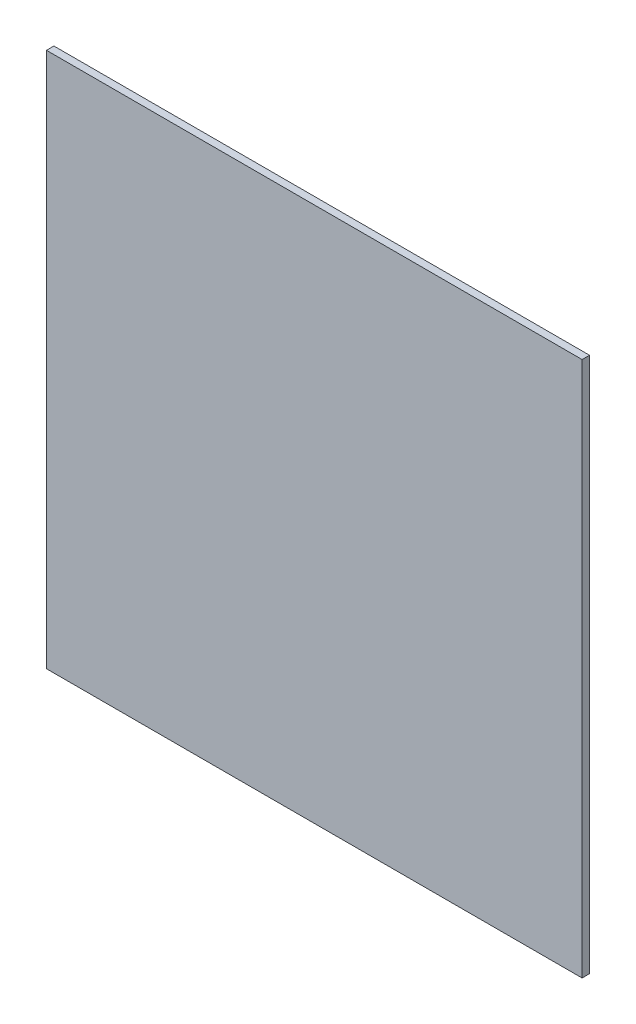
SolidWorks part; units mm, degrees
ref_plane "Front Plane" through (0, 0, 0) normal (0, 0, 1) x (1, 0, 0)
ref_plane "Top Plane" through (0, 0, 0) normal (0, 1, 0) x (1, 0, 0)
ref_plane "Right Plane" through (0, 0, 0) normal (1, 0, 0) x (0, 0, -1)
sketch "Sketch1" plane through (0, 0, 0) normal (0, 0, 1) x (1, 0, 0)
  line L0 (-20.2074, 1527.3098) -> (183.5006, 1527.3098) construction
  line L1 (-146.9534, 1527.3098) -> (310.2466, 1527.3098)
  line L2 (-146.9534, 1527.3098) -> (-146.9534, 1070.1098)
  line L3 (-146.9534, 1070.1098) -> (310.2466, 1070.1098)
  line L4 (310.2466, 1527.3098) -> (310.2466, 1070.1098)
  point P6 (81.6466, 1527.3098)
  dimension "D1" = 457.2
extrude "Boss-Extrude1" add sketch "Sketch1" along normal blind 6.35
